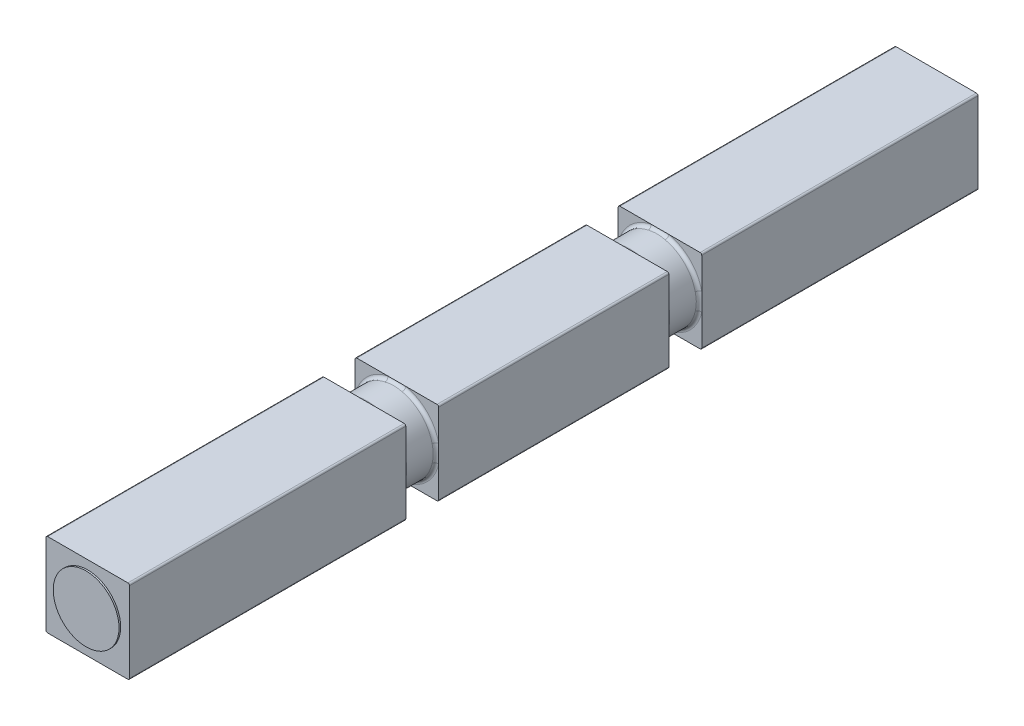
SolidWorks part; units mm, degrees
material "AISI 1010 Barra de acero laminada en caliente"
ref_plane "Alzado" through (0, 0, 0) normal (0, 0, 1) x (1, 0, 0)
ref_plane "Planta" through (0, 0, 0) normal (0, 1, 0) x (1, 0, 0)
ref_plane "Vista lateral" through (0, 0, 0) normal (1, 0, 0) x (0, 0, -1)
sketch "Croquis1" plane through (0, 0, 0) normal (0, 0, 1) x (1, 0, 0)
  line L1 (-12.2, 12.7) -> (12.2, 12.7)
  line L2 (-12.7, 12.2) -> (-12.7, -12.2)
  line L3 (-12.2, -12.7) -> (12.2, -12.7)
  line L4 (12.7, 12.2) -> (12.7, -12.2)
  line L5 (-12.7, 12.7) -> (12.7, -12.7) construction
  line L6 (-12.7, -12.7) -> (12.7, 12.7) construction
  arc A0 (12.2, -12.7) -> (12.7, -12.2) centre (12.2, -12.2) ccw
  arc A1 (-12.7, -12.2) -> (-12.2, -12.7) centre (-12.2, -12.2) ccw
  arc A2 (12.2, 12.7) -> (12.7, 12.2) centre (12.2, 12.2) cw
  arc A3 (-12.2, 12.7) -> (-12.7, 12.2) centre (-12.2, 12.2) ccw
  point P0 (0, 0)
  dimension "D3" = 0.5
  dimension "D1" = 25.4
  dimension "D2" = 25.4
extrude "Saliente-Extruir1" add sketch "Croquis1" along normal mid plane 258
sketch "Croquis2" plane through (0, 0, 0) normal (1, 0, 0) x (0, 0, -1)
  line L0 (0, 0) -> (0, 12.2) construction
  line L1 (-129, 12.2) -> (129, 12.2) construction
  line L2 (45, 22) -> (35, 22)
  line L3 (-45, 12) -> (-35, 12)
  line L4 (-45, 12) -> (-45, 22)
  line L5 (-45, 22) -> (-35, 22)
  line L6 (-35, 12) -> (-35, 22)
  line L7 (-45, 12) -> (-35, 22) construction
  line L8 (-45, 22) -> (-35, 12) construction
  line L9 (0, 0) -> (18.5373, 0) construction
  line L10 (35, 12) -> (35, 22)
  line L11 (45, 12) -> (35, 12)
  line L12 (45, 12) -> (45, 22)
  point P5 (-40, 17)
  dimension "D1" = 10
  dimension "D2" = 10
  dimension "D3" = 12
  dimension "D4" = 35
revolve "Cortar-Revolución1" cut sketch "Croquis2" angle 360 about L9
sketch "Croquis4" plane through (0, 0, 129) normal (0, 0, 1) x (1, 0, 0)
  circle A0 centre (0, 0) radius 10
  dimension "D1" = 20
extrude "Saliente-Extruir3" add sketch "Croquis4" along normal blind 0.5
mirror "Simetría1" about plane through (0, 0, 0) normal (0, 0, 1) of "Saliente-Extruir3"
fillet "Redondeo1" radius 1 4 edges at (12, 0, -45) (12, 0, -35) (12, 0, 35) (12, 0, 45)
